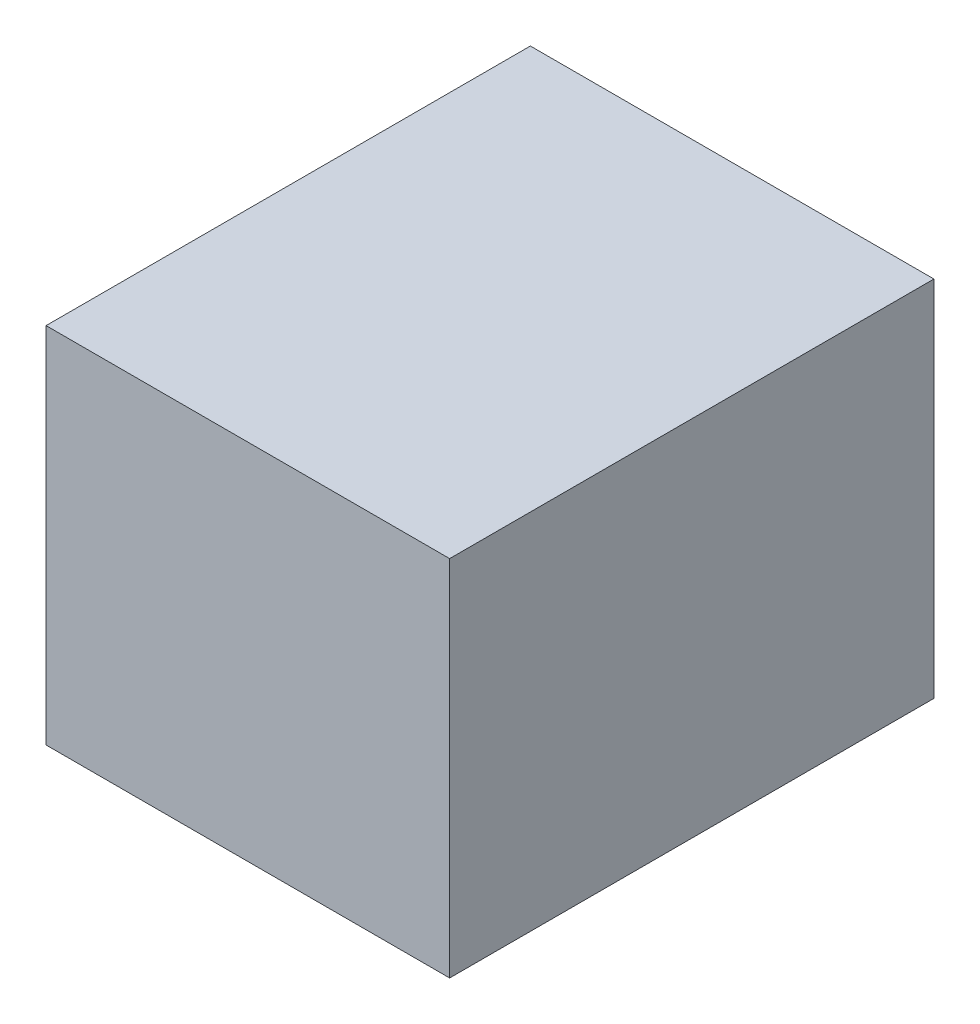
SolidWorks part; units mm, degrees
ref_plane "Спереди" through (0, 0, 0) normal (0, 0, 1) x (1, 0, 0)
ref_plane "Сверху" through (0, 0, 0) normal (0, 1, 0) x (1, 0, 0)
ref_plane "Справа" through (0, 0, 0) normal (1, 0, 0) x (0, 0, -1)
sketch "Эскиз1" plane through (0, 0, 0) normal (0, 0, 1) x (1, 0, 0)
  line L1 (-50, 45) -> (50, 45)
  line L2 (-50, 45) -> (-50, -45)
  line L3 (-50, -45) -> (50, -45)
  line L4 (50, 45) -> (50, -45)
  line L5 (-50, 45) -> (50, -45) construction
  line L6 (-50, -45) -> (50, 45) construction
  point P0 (0, 0)
  dimension "D1" = 90
  dimension "D2" = 100
extrude "Бобышка-Вытянуть2" add sketch "Эскиз1" along normal blind 120
equation "\"a\"=90"
equation "\"D1@Эскиз1\"=\"a\""
equation "\"b\"=100"
equation "\"D2@Эскиз1\"=\"b\""
equation "\"v\"=120"
equation "\"D1@Бобышка-Вытянуть2\"=\"v\""
